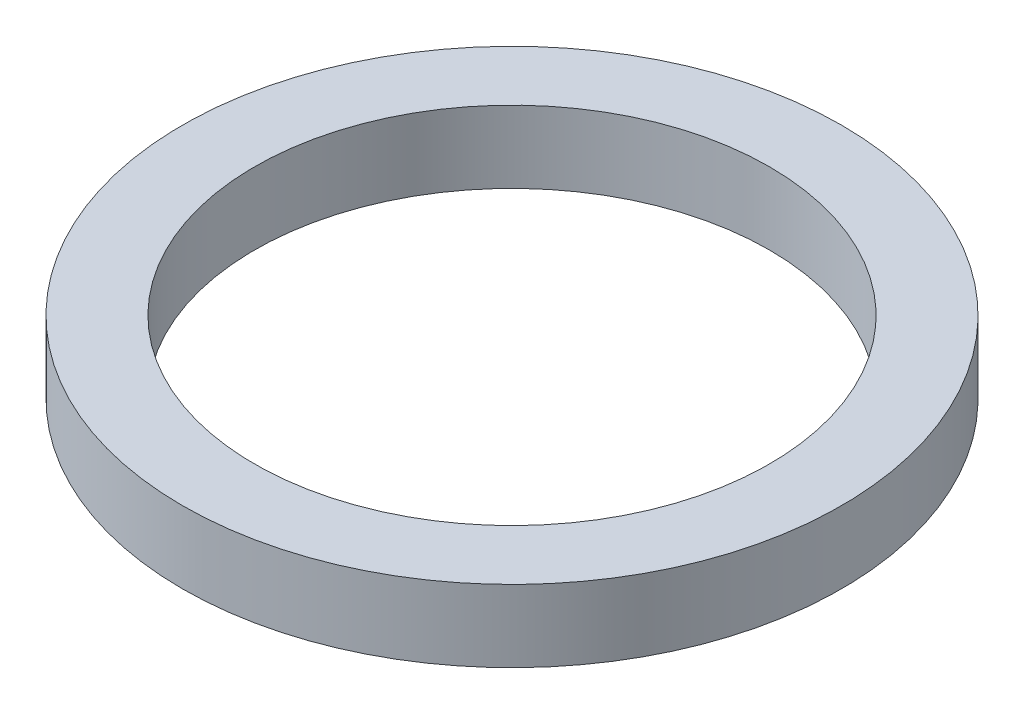
SolidWorks part; units mm, degrees
ref_plane "Plane1" through (0, 0, 0) normal (0, 0, 1) x (1, 0, 0)
ref_plane "Plane2" through (0, 0, 0) normal (0, 1, 0) x (1, 0, 0)
ref_plane "Plane3" through (0, 0, 0) normal (1, 0, 0) x (0, 0, -1)
sketch "Esquisse1" plane through (0, 0, 0) normal (0, 0, 1) x (1, 0, 0)
  line L0 (0, 0) -> (-3.5, 0)
  line L1 (0, 0) -> (0, 3.5)
  line L2 (-3.5, 3.5) -> (0, 3.5)
  line L3 (-3.5, 3.5) -> (-3.5, 0)
  dimension "D1" = 3.5
  dimension "D2" = 3.5
sketch "Esquisse2" plane through (0, 0, 0) normal (0, 1, 0) x (1, 0, 0)
  circle A0 centre (-16, 0) radius 16
sweep "segment" add profiles "Esquisse1" path "Esquisse2"
